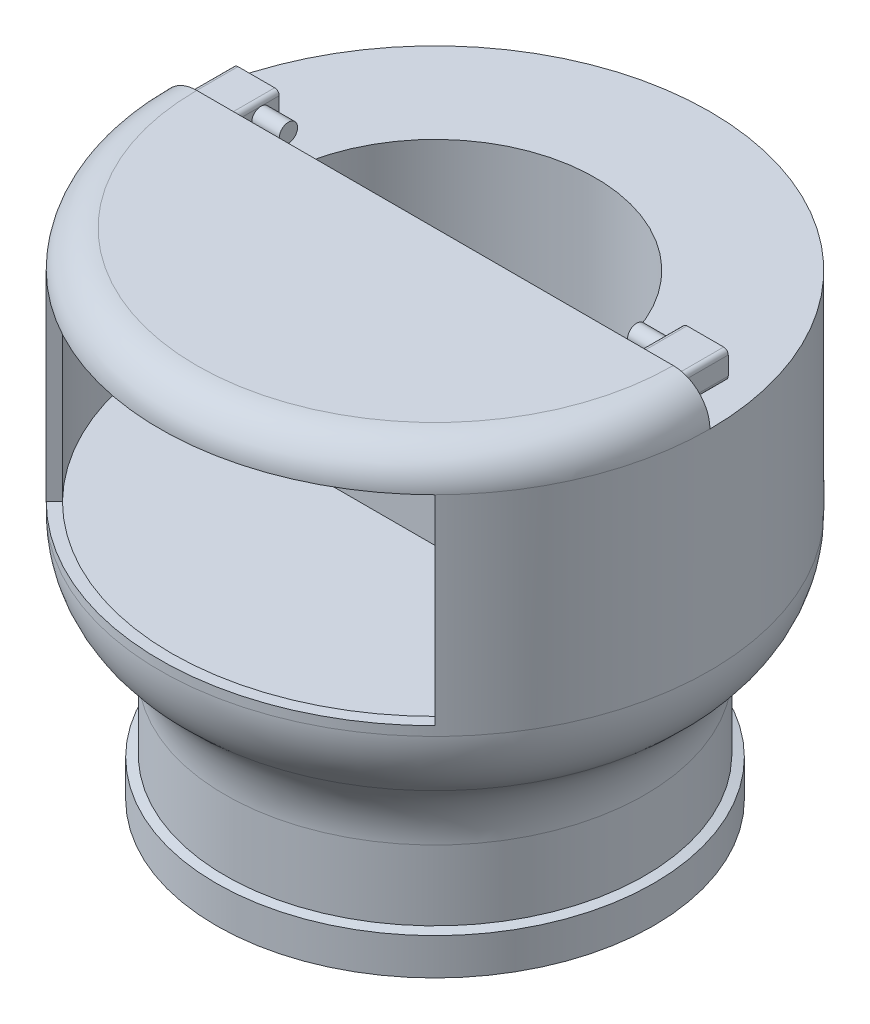
SolidWorks part; units mm, degrees
ref_plane "Front Plane" through (0, 0, 0) normal (0, 0, 1) x (1, 0, 0)
ref_plane "Top Plane" through (0, 0, 0) normal (0, 1, 0) x (1, 0, 0)
ref_plane "Right Plane" through (0, 0, 0) normal (1, 0, 0) x (0, 0, -1)
sketch "Sketch1" plane through (0, 0, 0) normal (0, 0, 1) x (1, 0, 0)
  line L0 (0, 0) -> (0, 57.8936) construction
  line L1 (20.9, 0) -> (23.8716, 0)
  line L2 (23.8716, 0) -> (23.8716, 4)
  line L3 (23.8716, 4) -> (22.9, 4.2367)
  line L4 (22.9, 4.2367) -> (22.9, 11.8746)
  line L6 (20.9, 0) -> (20.9, 14)
  line L12 (19.9, 15) -> (0, 15)
  line L17 (26.4721, 19.535) -> (26.4279, 19.4979)
  line L18 (30, 27.1583) -> (30, 50)
  line L20 (26, 54) -> (0, 54)
  line L22 (0, 15) -> (0, 54)
  arc A1 (30, 50) -> (26, 54) centre (26, 50) ccw
  arc A2 (26.4721, 19.535) -> (22.9, 11.8746) centre (32.9, 11.8746) ccw
  arc A3 (26.4279, 19.4979) -> (30, 27.1583) centre (20, 27.1583) ccw
  arc A6 (20.9, 14) -> (19.9, 15) centre (19.9, 14) ccw
  point P11 (22.9, 54)
  point P28 (28.5604, 23.4279)
  point P31 (20.9, 17)
  dimension "D9" = 4
  dimension "D4" = 30
  dimension "D16" = 10
  dimension "D19" = 1
  dimension "D2" = 4
  dimension "D3" = 1
  dimension "D6" = 2
  dimension "D7" = 2.9716
  dimension "D11" = 15
  dimension "D15" = 10
revolve "Revolve1" add sketch "Sketch1" angle 360 about L0
ref_plane "Plane1" through (0, 4, 0) normal (0, 1, 0) x (1, 0, 0)
sketch "Sketch3" plane through (0, 0, 0) normal (0, 0, 1) x (1, 0, 0)
  point P0 (1.2404, 19.1989)
ref_point "Point1"
ref_plane "Plane2" through (0, 0, 22.9) normal (0, 0, 1) x (1, 0, 0)
ref_plane "Plane3" through (0, 0, 30) normal (0, 0, 1) x (1, 0, 0)
ref_plane "Plane4" through (0, 50, 0) normal (0, -1, 0) x (-1, 0, 0)
sketch "Sketch9" plane through (0, 50, 0) normal (0, -1, 0) x (-1, 0, 0)
  line L0 (-30, 0) -> (30, 0)
  arc A0 (30, 0) -> (-30, 0) centre (0, 0) ccw
  circle A3 centre (0, 0) radius 26 construction
  dimension "D1" = 60
  dimension "D3" = 30
  dimension "D4" = 0
ref_plane "Plane5" through (0, 17, 0) normal (0, 1, 0) x (1, 0, 0)
sketch "Sketch11" plane through (0, 17, 0) normal (0, 1, 0) x (1, 0, 0)
  line L0 (-17.5, 0) -> (17.5, 0)
  arc A1 (-17.5, 0) -> (17.5, 0) centre (0, 0) cw
  dimension "D1" = 35
extrude "Cut-Extrude3" cut sketch "Sketch11" against normal blind 20 and the other way blind 45
ref_plane "Plane6" through (0, 0, -30) normal (0, 0, -1) x (-1, 0, 0)
extrude "Cut-Extrude5" cut sketch "Sketch9" against normal blind 5
sketch "Sketch13" plane through (0, 0, 0) normal (0, 0, -1) x (-1, 0, 0)
  line L0 (30, 49) -> (17.5, 49) construction
  line L1 (22.5, 53.5) -> (26.5, 53.5)
  line L2 (22, 53) -> (22, 51)
  line L3 (22.5, 50.5) -> (26.5, 50.5)
  line L4 (27, 53) -> (27, 51)
  line L5 (22, 53.5) -> (27, 50.5) construction
  line L6 (22, 50.5) -> (27, 53.5) construction
  line L7 (30, 49) -> (30, 50) construction
  line L8 (-30, 50) -> (-30, 49) construction
  line L9 (-26.5, 53.5) -> (-22.5, 53.5)
  line L10 (-27, 53) -> (-27, 51)
  line L11 (-26.5, 50.5) -> (-22.5, 50.5)
  line L12 (-22, 53) -> (-22, 51)
  line L13 (-27, 53.5) -> (-22, 50.5) construction
  line L14 (-27, 50.5) -> (-22, 53.5) construction
  line L15 (-17.5, 49) -> (-30, 49) construction
  arc A0 (26.5, 50.5) -> (27, 51) centre (26.5, 51) ccw
  arc A1 (27, 53) -> (26.5, 53.5) centre (26.5, 53) ccw
  arc A2 (22.5, 53.5) -> (22, 53) centre (22.5, 53) ccw
  arc A3 (22, 51) -> (22.5, 50.5) centre (22.5, 51) ccw
  arc A4 (-26.5, 53.5) -> (-27, 53) centre (-26.5, 53) ccw
  arc A5 (-27, 51) -> (-26.5, 50.5) centre (-26.5, 51) ccw
  arc A6 (-22.5, 50.5) -> (-22, 51) centre (-22.5, 51) ccw
  arc A7 (-22.5, 53.5) -> (-22, 53) centre (-22.5, 53) cw
  point P0 (24.5, 52)
  point P7 (-24.5, 52)
  dimension "D9" = 0.5
  dimension "D1" = 3
  dimension "D2" = 3
  dimension "D3" = 3
  dimension "D4" = 5
  dimension "D5" = 5
  dimension "D6" = 3
  dimension "D7" = 3
  dimension "D8" = 3
extrude "Boss-Extrude2" add sketch "Sketch13" along normal blind 5
sketch "Sketch14" plane through (22, 0, 0) normal (-1, 0, 0) x (0, 0, 1)
  line L0 (-5, 51) -> (0, 51) construction
  line L1 (-5, 51) -> (-5, 53) construction
  circle A0 centre (-3, 52) radius 1
  dimension "D1" = 2
  dimension "D2" = 1
  dimension "D3" = 2
extrude "Boss-Extrude3" add sketch "Sketch14" along normal blind 3
sketch "Sketch15" plane through (-22, 0, 0) normal (1, 0, 0) x (0, 0, -1)
  line L0 (5, 53) -> (0, 53) construction
  line L1 (5, 53) -> (5, 51) construction
  circle A0 centre (3, 52) radius 1
  dimension "D1" = 2
  dimension "D2" = 1
  dimension "D3" = 2
extrude "Boss-Extrude4" add sketch "Sketch15" along normal blind 3
sketch "Sketch16" plane through (0, 50, 0) normal (0, -1, 0) x (-1, 0, 0)
  line L0 (28.4704, -4) -> (-28.4704, -4)
  arc A0 (-28.4704, -4) -> (28.4704, -4) centre (0, 0) ccw
  arc A1 (-30, 0) -> (30, 0) centre (0, 0) ccw construction
  dimension "D1" = 1.25
  dimension "D2" = 4
  dimension "D3" = 4
extrude "Cut-Extrude6" cut sketch "Sketch16" along normal blind 22
sketch "Sketch18" plane through (0, 0, 0) normal (1, 0, 0) x (0, 0, -1)
  line L0 (-30, 28.173) -> (-28.5, 28.173)
  line L1 (-30, 12.5629) -> (-30, -12.5629) construction
  line L2 (-28.5, 28.173) -> (-28.5, 50)
  line L3 (-16.5, 50) -> (16.5, 50) construction
  line L4 (-28.5, 50) -> (-30, 50)
  line L5 (-30, 50) -> (-30, 28.173)
  line L7 (0, 0) -> (0, 69.381) construction
  dimension "D1" = 1.5
sketch "Sketch19" plane through (0, 50, 0) normal (0, -1, 0) x (-1, 0, 0)
  circle A0 centre (0, 0) radius 27.714 construction
sketch "Sketch20" plane through (0, 0, 0) normal (1, 0, 0) x (0, 0, -1)
  line L0 (0, 0) -> (0, 98.284) construction
revolve "Cut-Revolve1" cut sketch "Sketch18" angle 45 about L7 other way angle 45
